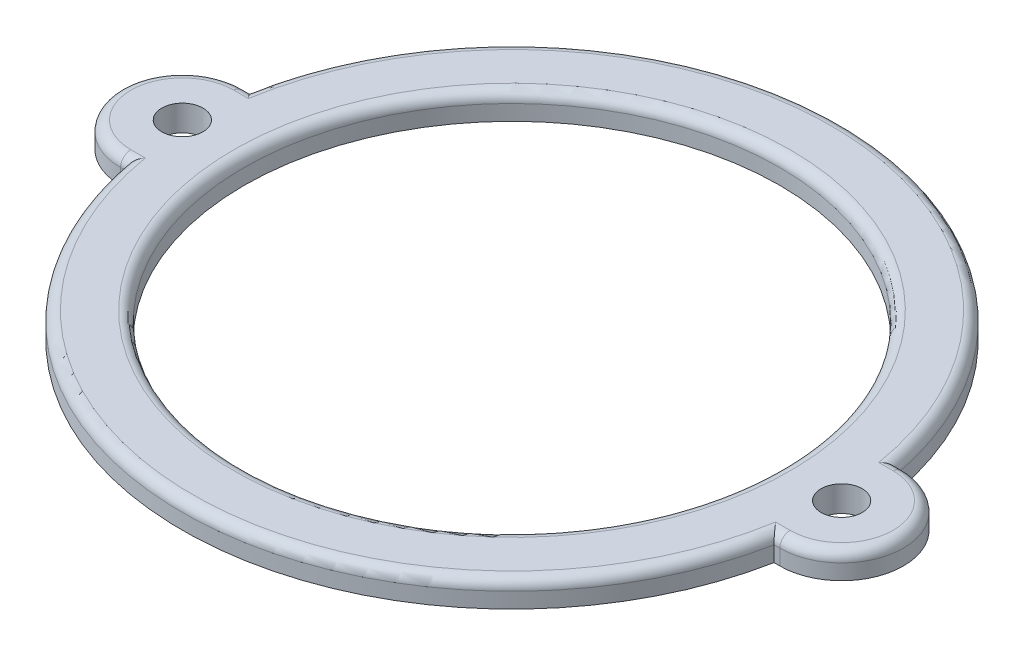
SolidWorks part; units mm, degrees
ref_plane "Alzado" through (0, 0, 0) normal (0, 0, 1) x (1, 0, 0)
ref_plane "Planta" through (0, 0, 0) normal (0, 1, 0) x (1, 0, 0)
ref_plane "Vista lateral" through (0, 0, 0) normal (1, 0, 0) x (0, 0, -1)
sketch "Croquis1" plane through (0, 0, 0) normal (0, 1, 0) x (1, 0, 0)
  line L0 (-32, 0) -> (32, 0) construction
  line L1 (-32, 6) -> (-31.4325, 6)
  line L2 (-32, -6) -> (-31.4325, -6)
  line L3 (0, 32) -> (0, -32) construction
  line L4 (32, 6) -> (31.4325, 6)
  line L5 (32, -6) -> (31.4325, -6)
  circle A0 centre (0, 0) radius 26
  circle A2 centre (-32, 0) radius 2
  arc A8 (-32, 6) -> (-32, -6) centre (-32, 0) ccw
  arc A9 (-31.4325, -6) -> (31.4325, -6) centre (0, 0) ccw
  arc A11 (32, 6) -> (32, -6) centre (32, 0) cw
  arc A12 (31.4325, 6) -> (-31.4325, 6) centre (0, 0) ccw
  circle A13 centre (32, 0) radius 2
  point P6 (0, 0)
  point P20 (-38, 0)
  dimension "D2" = 4
  dimension "D3" = 4
  dimension "D4" = 32
  dimension "D12" = 52
  dimension "D14" = 6
  dimension "D1" = 64
extrude "Saliente-Extruir1" add sketch "Croquis1" along normal blind 2.5
fillet "Redondeo1" radius 1 9 edges at (0, 2.5, 26) (31.7162, 2.5, 6) (0, 2.5, 32) (-31.7162, 2.5, 6) (-38, 2.5, 0) (-31.7162, 2.5, -6) (0, 2.5, -32) (31.7162, 2.5, -6) (38, 2.5, 0)
